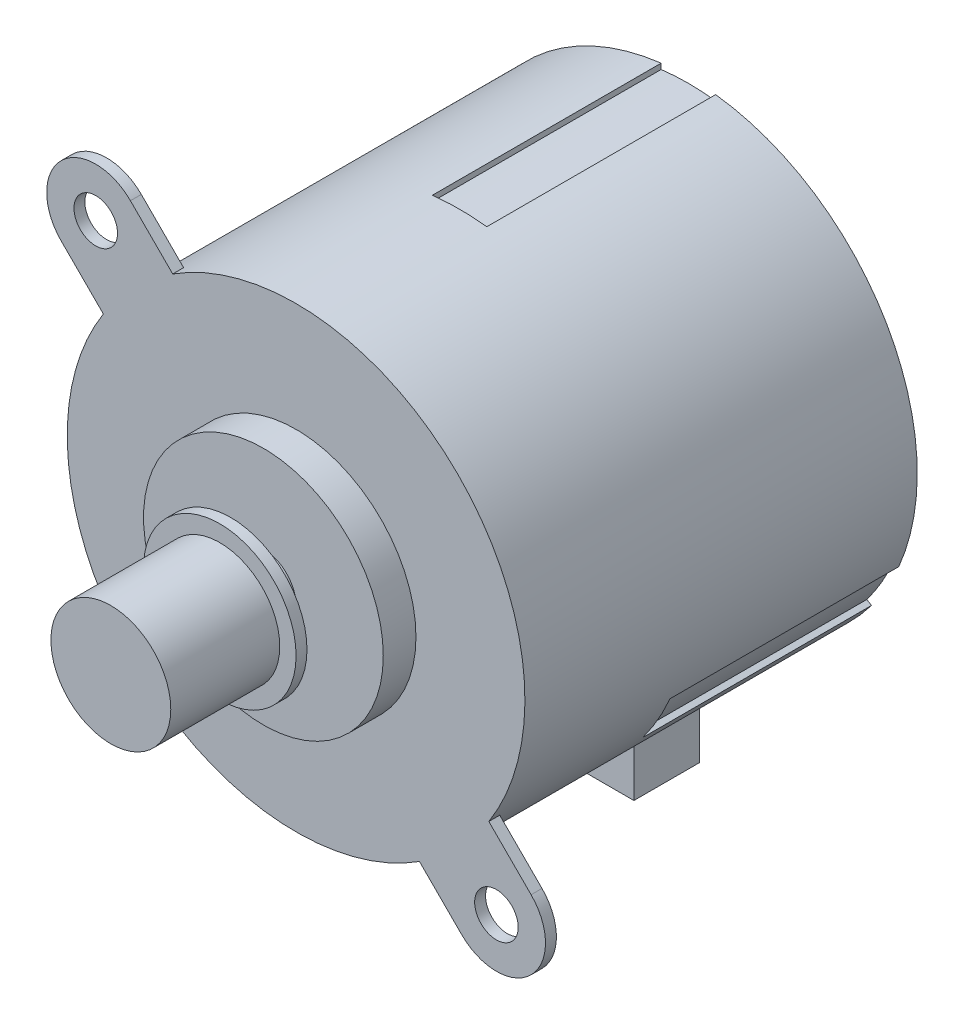
SolidWorks part; units mm, degrees
ref_plane "前视基准面" through (0, 0, 0) normal (0, 0, 1) x (1, 0, 0)
ref_plane "上视基准面" through (0, 0, 0) normal (0, 1, 0) x (1, 0, 0)
ref_plane "右视基准面" through (0, 0, 0) normal (1, 0, 0) x (0, 0, -1)
other "Configuration Table"
sketch "草图1" plane through (0, 0, 0) normal (0, 0, 1) x (1, 0, 0)
  circle A0 centre (0, 0) radius 21
extrude "凸台-拉伸1" add sketch "草图1" along normal blind 15
sketch "草图2" plane through (0, 0, 0) normal (0, 0, -1) x (-1, 0, 0)
  line L0 (2.5, 20.8507) -> (2.5, 20.347)
  line L1 (0, 8.25) -> (0, -8.25) construction
  line L2 (-2.5, 20.8507) -> (-2.5, 20.347)
  line L3 (19.3072, -8.2603) -> (18.871, -8.0084)
  line L4 (16.8072, -12.5904) -> (16.371, -12.3386)
  line L5 (-16.8072, -12.5904) -> (-16.371, -12.3386)
  line L6 (-19.3072, -8.2603) -> (-18.871, -8.0084)
  line L7 (15, -13.9732) -> (15, -14.6969)
  line L8 (-15, -13.9732) -> (-15, -14.6969)
  arc A0 (-2.5, 20.8507) -> (-19.3072, -8.2603) centre (0, 0) ccw
  circle A1 centre (0, 0) radius 21 construction
  arc A2 (-18.871, -8.0084) -> (-16.371, -12.3386) centre (0, 0) ccw
  arc A3 (19.3072, -8.2603) -> (2.5, 20.8507) centre (0, 0) ccw
  arc A4 (-16.8072, -12.5904) -> (-15, -14.6969) centre (0, 0) ccw
  arc A5 (15, -14.6969) -> (16.8072, -12.5904) centre (0, 0) ccw
  arc A6 (-15, -13.9732) -> (15, -13.9732) centre (0, 0) ccw
  arc A7 (16.371, -12.3386) -> (18.871, -8.0084) centre (0, 0) ccw
  arc A8 (2.5, 20.347) -> (-2.5, 20.347) centre (0, 0) ccw
  point P22 (0, 0)
  dimension "D1" = 5
  dimension "D2" = 3
  dimension "D3" = 30
extrude "凸台-拉伸2" add sketch "草图2" along normal blind 6
sketch "草图4" plane through (0, 0, -6) normal (0, 0, -1) x (-1, 0, 0)
  line L0 (10, -17.8955) -> (10, -24)
  line L1 (0, 11.55) -> (0, -11.55) construction
  line L2 (-10, -17.8955) -> (-10, -24)
  line L3 (-10, -24) -> (10, -24)
  line L8 (2.5, 20.8507) -> (2.5, 20.347)
  line L9 (-2.5, 20.347) -> (-2.5, 20.8507)
  line L10 (-19.3072, -8.2603) -> (-18.871, -8.0084)
  line L11 (-16.371, -12.3386) -> (-16.8072, -12.5904)
  line L12 (-15, -14.6969) -> (-15, -13.9732)
  line L13 (15, -13.9732) -> (15, -14.6969)
  line L14 (16.8072, -12.5904) -> (16.371, -12.3386)
  line L15 (18.871, -8.0084) -> (19.3072, -8.2603)
  line L16 (2.5, 20.8507) -> (2.5, 20.347)
  line L17 (-2.5, 20.347) -> (-2.5, 20.8507)
  line L18 (-19.3072, -8.2603) -> (-18.871, -8.0084)
  line L19 (-16.371, -12.3386) -> (-16.8072, -12.5904)
  line L20 (-15, -14.6969) -> (-15, -13.9732)
  line L21 (15, -13.9732) -> (15, -14.6969)
  line L22 (16.8072, -12.5904) -> (16.371, -12.3386)
  line L23 (18.871, -8.0084) -> (19.3072, -8.2603)
  arc A0 (10, -17.8955) -> (15, -13.9732) centre (0, 0) ccw
  arc A8 (19.3072, -8.2603) -> (2.5, 20.8507) centre (0, 0) ccw
  arc A9 (2.5, 20.347) -> (-2.5, 20.347) centre (0, 0) ccw
  arc A10 (-2.5, 20.8507) -> (-19.3072, -8.2603) centre (0, 0) ccw
  arc A11 (-18.871, -8.0084) -> (-16.371, -12.3386) centre (0, 0) ccw
  arc A12 (-16.8072, -12.5904) -> (-15, -14.6969) centre (0, 0) ccw
  arc A13 (-15, -13.9732) -> (15, -13.9732) centre (0, 0) ccw
  arc A14 (15, -14.6969) -> (16.8072, -12.5904) centre (0, 0) ccw
  arc A15 (16.371, -12.3386) -> (18.871, -8.0084) centre (0, 0) ccw
  arc A16 (19.3072, -8.2603) -> (2.5, 20.8507) centre (0, 0) ccw
  arc A17 (2.5, 20.347) -> (-2.5, 20.347) centre (0, 0) ccw
  arc A18 (-2.5, 20.8507) -> (-19.3072, -8.2603) centre (0, 0) ccw
  arc A19 (-18.871, -8.0084) -> (-16.371, -12.3386) centre (0, 0) ccw
  arc A20 (-16.8072, -12.5904) -> (-15, -14.6969) centre (0, 0) ccw
  arc A21 (-15, -13.9732) -> (-10, -17.8955) centre (0, 0) ccw
  arc A22 (15, -14.6969) -> (16.8072, -12.5904) centre (0, 0) ccw
  arc A23 (16.371, -12.3386) -> (18.871, -8.0084) centre (0, 0) ccw
  dimension "D2" = 20
  dimension "D3" = 24
  dimension "D1" = 0
extrude "凸台-拉伸3" add sketch "草图4" along normal blind 6
sketch "草图5" plane through (0, 0, -12) normal (0, 0, -1) x (-1, 0, 0)
  line L8 (18.871, -8.0084) -> (19.3072, -8.2603)
  line L9 (2.5, 20.8507) -> (2.5, 20.347)
  line L10 (-2.5, 20.347) -> (-2.5, 20.8507)
  line L11 (-19.3072, -8.2603) -> (-18.871, -8.0084)
  line L12 (-16.371, -12.3386) -> (-16.8072, -12.5904)
  line L13 (-15, -14.6969) -> (-15, -13.9732)
  line L14 (15, -13.9732) -> (15, -14.6969)
  line L15 (16.8072, -12.5904) -> (16.371, -12.3386)
  line L16 (18.871, -8.0084) -> (19.3072, -8.2603)
  line L17 (2.5, 20.8507) -> (2.5, 20.347)
  line L18 (-2.5, 20.347) -> (-2.5, 20.8507)
  line L19 (-19.3072, -8.2603) -> (-18.871, -8.0084)
  line L20 (-16.371, -12.3386) -> (-16.8072, -12.5904)
  line L23 (16.8072, -12.5904) -> (16.371, -12.3386)
  arc A0 (-15, -14.6969) -> (15, -14.6969) centre (0, 0) ccw
  arc A1 (-15, -14.6969) -> (15, -14.6969) centre (0, 0) ccw construction
  arc A8 (19.3072, -8.2603) -> (2.5, 20.8507) centre (0, 0) ccw
  arc A9 (2.5, 20.347) -> (-2.5, 20.347) centre (0, 0) ccw
  arc A10 (-2.5, 20.8507) -> (-19.3072, -8.2603) centre (0, 0) ccw
  arc A11 (-18.871, -8.0084) -> (-16.371, -12.3386) centre (0, 0) ccw
  arc A12 (-16.8072, -12.5904) -> (-15, -14.6969) centre (0, 0) ccw
  arc A13 (-15, -13.9732) -> (15, -13.9732) centre (0, 0) ccw
  arc A14 (15, -14.6969) -> (16.8072, -12.5904) centre (0, 0) ccw
  arc A15 (16.371, -12.3386) -> (18.871, -8.0084) centre (0, 0) ccw
  arc A16 (19.3072, -8.2603) -> (2.5, 20.8507) centre (0, 0) ccw
  arc A17 (2.5, 20.347) -> (-2.5, 20.347) centre (0, 0) ccw
  arc A18 (-2.5, 20.8507) -> (-19.3072, -8.2603) centre (0, 0) ccw
  arc A19 (-18.871, -8.0084) -> (-16.371, -12.3386) centre (0, 0) ccw
  arc A20 (-16.8072, -12.5904) -> (-15, -14.6969) centre (0, 0) ccw
  arc A22 (15, -14.6969) -> (16.8072, -12.5904) centre (0, 0) ccw
  arc A23 (16.371, -12.3386) -> (18.871, -8.0084) centre (0, 0) ccw
  dimension "D1" = 0
extrude "凸台-拉伸4" add sketch "草图5" along normal blind 9
sketch "草图6" plane through (0, 0, 15) normal (0, 0, 1) x (1, 0, 0)
  circle A0 centre (0, 0) radius 11
  dimension "D1" = 22
extrude "凸台-拉伸5" add sketch "草图6" along normal blind 3
sketch "草图7" plane through (0, 0, 18) normal (0, 0, 1) x (1, 0, 0)
  circle A0 centre (0, 0) radius 3
extrude "凸台-拉伸6" add sketch "草图7" along normal blind 14
sketch "草图8" plane through (0, 0, 15) normal (0, 0, 1) x (1, 0, 0)
  line L0 (0, 0) -> (24.2424, -24.2424) construction
  line L1 (-15.2028, 21.5668) -> (-11.3223, 17.6863)
  line L2 (-21.5668, 15.2028) -> (-17.6863, 11.3223)
  line L3 (11.3223, -17.6863) -> (15.2028, -21.5668)
  line L4 (17.6863, -11.3223) -> (21.5668, -15.2028)
  circle A0 centre (0, 0) radius 26 construction
  circle A2 centre (18.3848, -18.3848) radius 2
  circle A3 centre (-18.3848, 18.3848) radius 2
  arc A4 (14.9394, -21.2795) -> (21.2795, -14.9394) centre (18.3848, -18.3848) ccw
  arc A5 (-14.9394, 21.2795) -> (-21.2795, 14.9394) centre (-18.3848, 18.3848) ccw
  circle A8 centre (0, 0) radius 21 construction
  arc A9 (11.3223, -17.6863) -> (-17.6863, 11.3223) centre (0, 0) ccw
  point P10 (0, 0)
  dimension "D1" = 2
extrude "凸台-拉伸7" add sketch "草图8" against normal blind 1
sketch "草图9" plane through (0, 0, 32) normal (0, 0, 1) x (1, 0, 0)
  circle A0 centre (0, 0) radius 7
  circle A1 centre (0, 0) radius 3
extrude "凸台-拉伸8" add sketch "草图9" against normal blind 11
sketch "草图10" plane through (0, 0, 32) normal (0, 0, 1) x (1, 0, 0)
  circle A0 centre (0, 0) radius 5.5
  circle A1 centre (0, 0) radius 7 construction
  circle A2 centre (0, 0) radius 7
  circle M2 centre (0, 0) radius 7
extrude "切除-拉伸1" cut sketch "草图10" against normal blind 10 contours A0 M2
